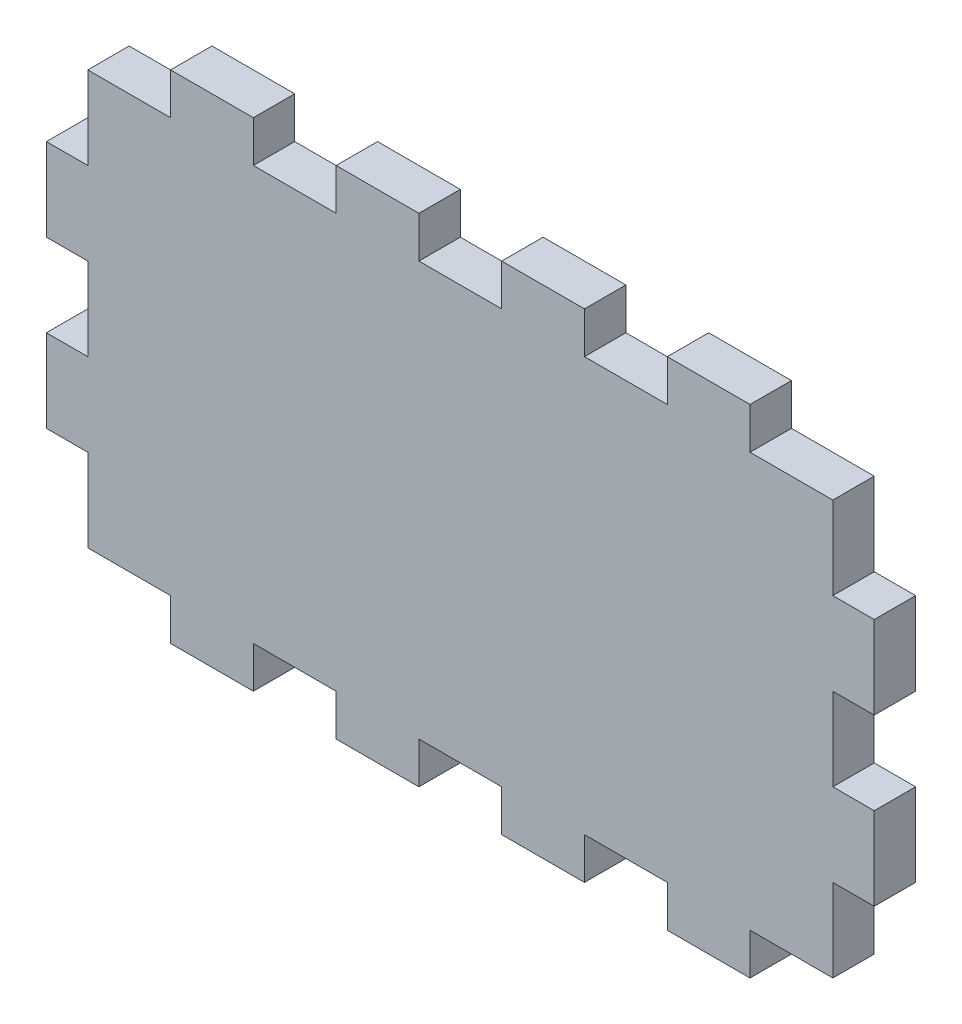
SolidWorks part; units mm, degrees
ref_plane "Front Plane" through (0, 0, 0) normal (0, 0, 1) x (1, 0, 0)
ref_plane "Top Plane" through (0, 0, 0) normal (0, 1, 0) x (1, 0, 0)
ref_plane "Right Plane" through (0, 0, 0) normal (1, 0, 0) x (0, 0, -1)
sketch "Sketch1" plane through (0, 0, 0) normal (0, 0, 1) x (1, 0, 0)
  line L1 (-204.7456, 156.5648) -> (-204.7456, 146.5648)
  line L2 (-204.7456, 146.5648) -> (-209.7456, 146.5648)
  line L3 (-209.7456, 146.5648) -> (-209.7456, 136.5648)
  line L4 (-209.7456, 136.5648) -> (-204.7456, 136.5648)
  line L5 (-204.7456, 136.5648) -> (-204.7456, 126.5648)
  line L6 (-204.7456, 126.5648) -> (-209.7456, 126.5648)
  line L7 (-209.7456, 126.5648) -> (-209.7456, 116.5648)
  line L8 (-209.7456, 116.5648) -> (-204.7456, 116.5648)
  line L9 (-204.7456, 116.5648) -> (-204.7456, 106.5648)
  line L10 (-204.7456, 106.5648) -> (-194.7456, 106.5648)
  line L11 (-194.7456, 106.5648) -> (-194.7456, 101.5648)
  line L12 (-194.7456, 101.5648) -> (-184.7456, 101.5648)
  line L13 (-184.7456, 101.5648) -> (-184.7456, 106.5648)
  line L14 (-184.7456, 106.5648) -> (-174.7456, 106.5648)
  line L15 (-174.7456, 106.5648) -> (-174.7456, 101.5648)
  line L16 (-174.7456, 101.5648) -> (-164.7456, 101.5648)
  line L17 (-164.7456, 101.5648) -> (-164.7456, 106.5648)
  line L18 (-164.7456, 106.5648) -> (-154.7456, 106.5648)
  line L19 (-154.7456, 106.5648) -> (-154.7456, 101.5648)
  line L20 (-154.7456, 101.5648) -> (-144.7456, 101.5648)
  line L21 (-144.7456, 101.5648) -> (-144.7456, 106.5648)
  line L22 (-144.7456, 106.5648) -> (-134.7456, 106.5648)
  line L23 (-134.7456, 106.5648) -> (-134.7456, 101.5648)
  line L24 (-134.7456, 101.5648) -> (-124.7456, 101.5648)
  line L25 (-124.7456, 101.5648) -> (-124.7456, 106.5648)
  line L26 (-124.7456, 106.5648) -> (-114.7456, 106.5648)
  line L27 (-114.7456, 106.5648) -> (-114.7456, 116.5648)
  line L28 (-114.7456, 116.5648) -> (-109.7456, 116.5648)
  line L29 (-109.7456, 116.5648) -> (-109.7456, 126.5648)
  line L30 (-109.7456, 126.5648) -> (-114.7456, 126.5648)
  line L31 (-114.7456, 126.5648) -> (-114.7456, 136.5648)
  line L32 (-114.7456, 136.5648) -> (-109.7456, 136.5648)
  line L33 (-109.7456, 136.5648) -> (-109.7456, 146.5648)
  line L34 (-109.7456, 146.5648) -> (-114.7456, 146.5648)
  line L35 (-114.7456, 146.5648) -> (-114.7456, 156.5648)
  line L36 (-114.7456, 156.5648) -> (-124.7456, 156.5648)
  line L37 (-124.7456, 156.5648) -> (-124.7456, 161.5648)
  line L38 (-124.7456, 161.5648) -> (-134.7456, 161.5648)
  line L39 (-134.7456, 161.5648) -> (-134.7456, 156.5648)
  line L40 (-134.7456, 156.5648) -> (-144.7456, 156.5648)
  line L41 (-144.7456, 156.5648) -> (-144.7456, 161.5648)
  line L42 (-144.7456, 161.5648) -> (-154.7456, 161.5648)
  line L43 (-154.7456, 161.5648) -> (-154.7456, 156.5648)
  line L44 (-154.7456, 156.5648) -> (-164.7456, 156.5648)
  line L45 (-164.7456, 156.5648) -> (-164.7456, 161.5648)
  line L46 (-164.7456, 161.5648) -> (-174.7456, 161.5648)
  line L47 (-174.7456, 161.5648) -> (-174.7456, 156.5648)
  line L48 (-174.7456, 156.5648) -> (-184.7456, 156.5648)
  line L49 (-184.7456, 156.5648) -> (-184.7456, 161.5648)
  line L50 (-184.7456, 161.5648) -> (-194.7456, 161.5648)
  line L51 (-194.7456, 161.5648) -> (-194.7456, 156.5648)
  line L52 (-194.7456, 156.5648) -> (-204.7456, 156.5648)
extrude "Boss-Extrude1" add sketch "Sketch1" along normal blind 5
